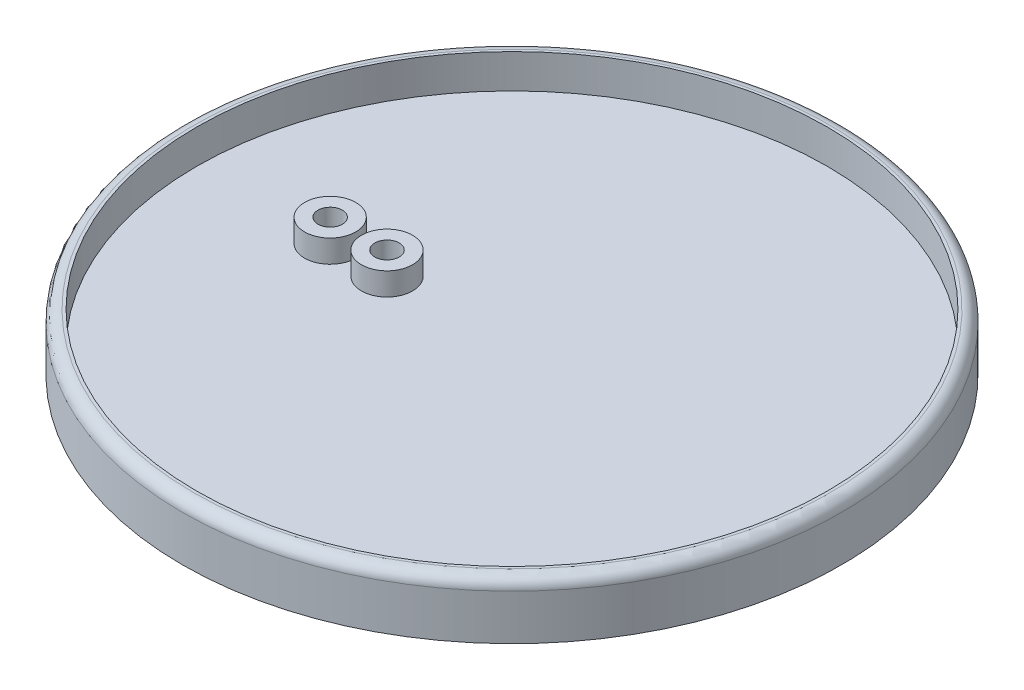
SolidWorks part; units mm, degrees
ref_plane "前视基准面" through (0, 0, 0) normal (0, 0, 1) x (1, 0, 0)
ref_plane "上视基准面" through (0, 0, 0) normal (0, 1, 0) x (1, 0, 0)
ref_plane "右视基准面" through (0, 0, 0) normal (1, 0, 0) x (0, 0, -1)
other "Configuration Table"
sketch "草图1" plane through (0, 0, 0) normal (0, 1, 0) x (1, 0, 0)
  circle A0 centre (-22, 0) radius 4.5
extrude "Moving_post_A" add sketch "草图1" along normal blind 8
sketch "草图2" plane through (0, 0, 0) normal (0, 1, 0) x (1, 0, 0)
  circle A0 centre (0, 0) radius 58
extrude "Cup_plate_D116_T4" add sketch "草图2" along normal blind 4
sketch "草图3" plane through (0, 0, 0) normal (0, 1, 0) x (1, 0, 0)
  circle A0 centre (-32, 0) radius 4.5
extrude "Moving_post_B" add sketch "草图3" along normal blind 8
sketch "草图4" plane through (0, 0, 0) normal (0, 1, 0) x (1, 0, 0)
  circle A0 centre (0, 0) radius 58
  circle A1 centre (0, 0) radius 55.5
extrude "Drip_skirt_OD116_ID111_H10" add sketch "草图4" along normal blind 10
sketch "草图5" plane through (0, 0, 0) normal (0, 1, 0) x (1, 0, 0)
  circle A0 centre (-22, 0) radius 2.15
  circle A1 centre (-32, 0) radius 2.15
extrude "M4_moving_mount_clearance" cut sketch "草图5" along normal blind 8
fillet "Cup_top_outer_round_R2" radius 2 1 edges at (0, 10, 58)
